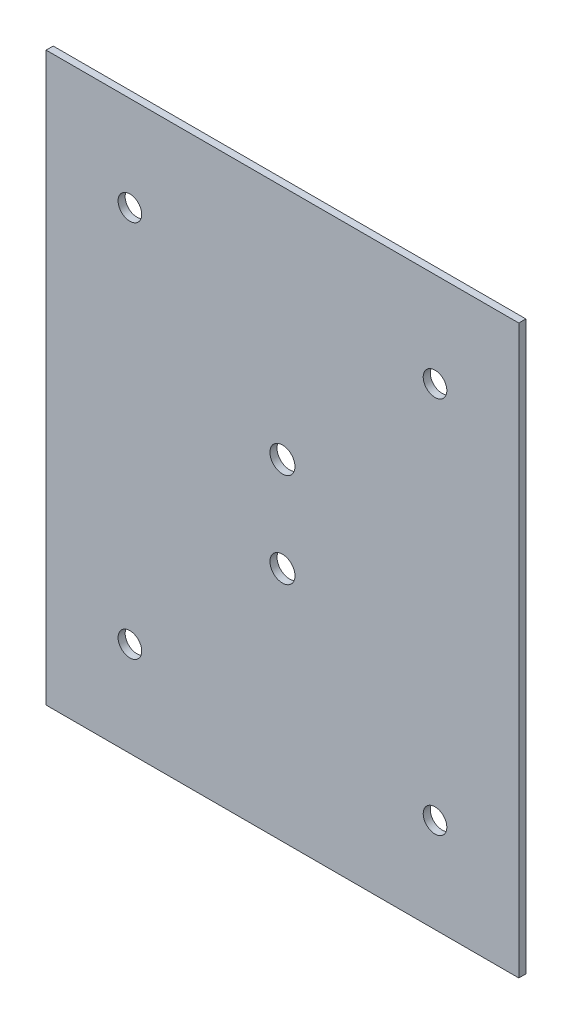
SolidWorks part; units mm, degrees
material "Stainless Steel (ferritic)"
ref_plane "Front Plane" through (0, 0, 0) normal (0, 0, 1) x (1, 0, 0)
ref_plane "Top Plane" through (0, 0, 0) normal (0, 1, 0) x (1, 0, 0)
ref_plane "Right Plane" through (0, 0, 0) normal (1, 0, 0) x (0, 0, -1)
sketch "Sketch1" plane through (0, 0, 0) normal (0, 0, 1) x (1, 0, 0)
  line L1 (0, 0) -> (100, 0)
  line L2 (0, 0) -> (0, 120)
  line L3 (0, 120) -> (100, 120)
  line L4 (100, 0) -> (100, 120)
  dimension "D1" = 120
  dimension "D2" = 100
extrude "Boss-Extrude1" add sketch "Sketch1" along normal blind 1.5
sketch "Sketch2" plane through (0, 0, 0) normal (0, 0, -1) x (-1, 0, 0)
  line L0 (-82.275, 100) -> (-17.725, 100) construction
  line L1 (-17.725, 100) -> (-17.725, 20) construction
  line L2 (-17.725, 20) -> (-82.275, 20) construction
  line L3 (-82.275, 20) -> (-82.275, 100) construction
  line L4 (-82.275, 100) -> (-100, 100) construction
  line L5 (-100, 0) -> (-100, 120) construction
  line L6 (-82.275, 100) -> (-82.275, 120) construction
  line L7 (-100, 120) -> (0, 120) construction
  line L8 (-17.725, 100) -> (-17.725, 120) construction
  line L9 (-17.725, 100) -> (0, 100) construction
  line L10 (0, 120) -> (0, 0) construction
  line L11 (-17.725, 20) -> (0, 20) construction
  line L12 (-17.725, 20) -> (-17.725, 0) construction
  line L13 (0, 0) -> (-100, 0) construction
  line L14 (-82.275, 20) -> (-82.275, 0) construction
  line L15 (-82.275, 20) -> (-100, 20) construction
  circle A0 centre (-82.275, 20) radius 2.5
  circle A1 centre (-17.725, 20) radius 2.5
  circle A2 centre (-17.725, 100) radius 2.5
  circle A3 centre (-82.275, 100) radius 2.5
  dimension "D1" = 5
  dimension "D2" = 17.725
  dimension "D3" = 20
extrude "Cut-Extrude1" cut sketch "Sketch2" against normal blind 1.5
sketch "Sketch4" plane through (0, 0, 1.5) normal (0, 0, 1) x (1, 0, 0)
  line L0 (50, 120) -> (50, 0) construction
  line L1 (0, 0) -> (100, 0)
  line L2 (0, 0) -> (0, 120)
  line L3 (0, 120) -> (100, 120)
  line L4 (100, 0) -> (100, 120)
  line L5 (50, 60) -> (50, 70) construction
  line L6 (50, 60) -> (50, 50) construction
  circle A0 centre (50, 70) radius 2.65
  circle A1 centre (50, 50) radius 2.65
  dimension "D2" = 5.3
  dimension "D3" = 5.3
  dimension "D1" = 20
extrude "Cut-Extrude2" cut sketch "Sketch4" against normal up to surface (1.5 mm away) contours A1 | A0 up to face at (79.775, 100, 0)
